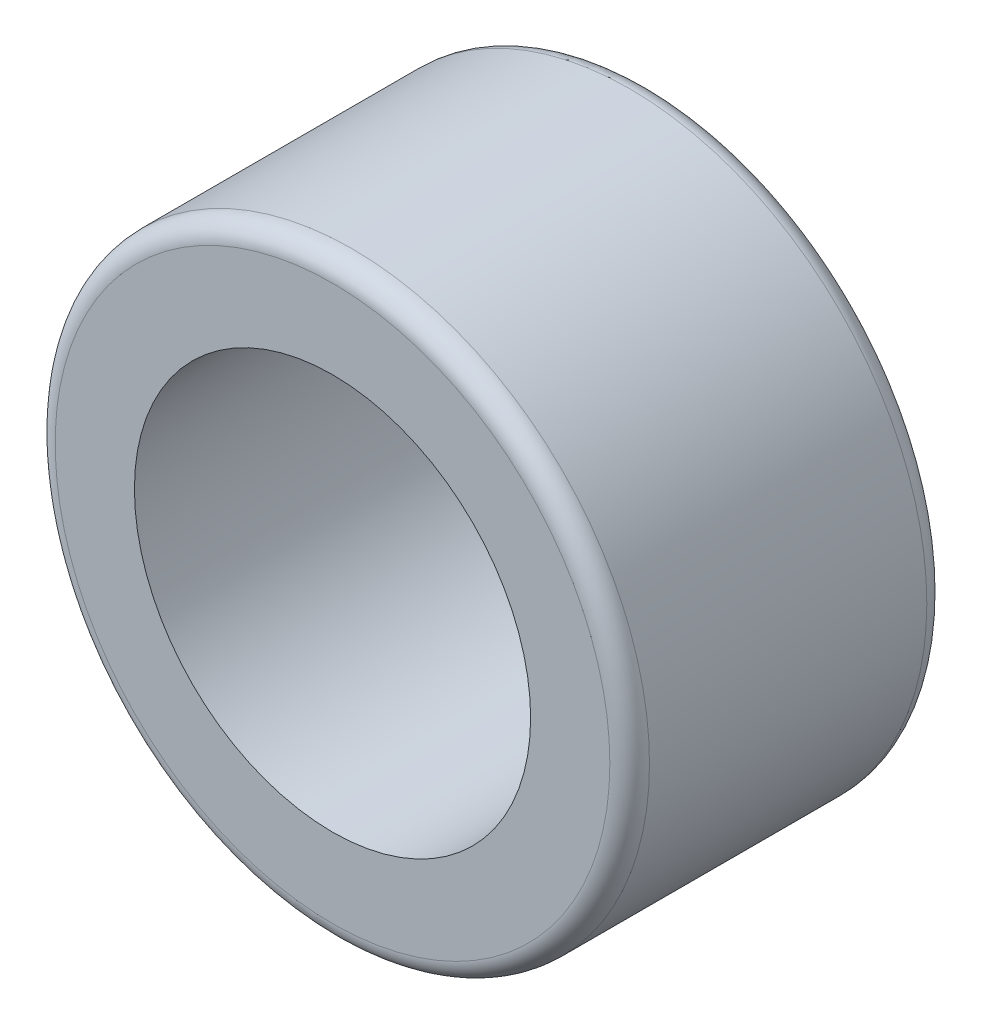
SolidWorks part; units mm, degrees
ref_plane "Front Plane" through (0, 0, 0) normal (0, 0, 1) x (1, 0, 0)
ref_plane "Top Plane" through (0, 0, 0) normal (0, 1, 0) x (1, 0, 0)
ref_plane "Right Plane" through (0, 0, 0) normal (1, 0, 0) x (0, 0, -1)
sketch "Sketch1" plane through (0, 0, 0) normal (0, 0, 1) x (1, 0, 0)
  circle A0 centre (0, 0) radius 7.5
  dimension "D1" = 15
extrude "Boss-Extrude1" add sketch "Sketch1" along normal blind 8
sketch "Sketch2" plane through (0, 0, 8) normal (0, 0, 1) x (1, 0, 0)
  circle A0 centre (0, 0) radius 5
  dimension "D1" = 10
extrude "Cut-Extrude1" cut sketch "Sketch2" against normal through all
fillet "Fillet1" radius 0.5 2 edges at (7.5, 0, 8) (7.5, 0, 0)
